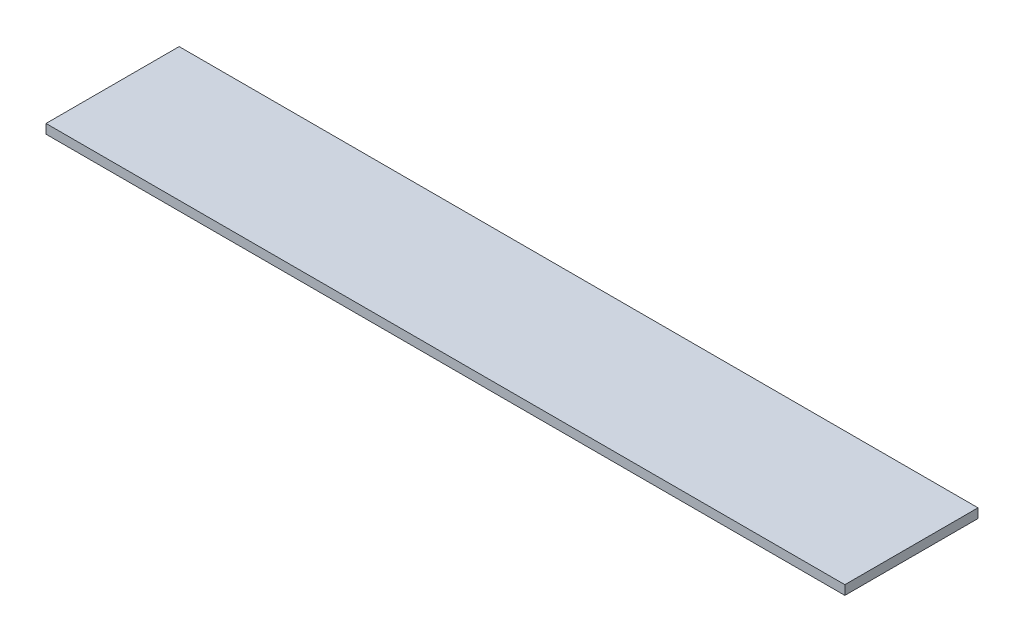
SolidWorks part; units mm, degrees
ref_plane "Front Plane" through (0, 0, 0) normal (0, 0, 1) x (1, 0, 0)
ref_plane "Top Plane" through (0, 0, 0) normal (0, 1, 0) x (1, 0, 0)
ref_plane "Right Plane" through (0, 0, 0) normal (1, 0, 0) x (0, 0, -1)
sketch "Sketch1" plane through (0, 0, 0) normal (0, 1, 0) x (1, 0, 0)
  line L1 (-30, -5) -> (30, -5)
  line L2 (-30, -5) -> (-30, 5)
  line L3 (-30, 5) -> (30, 5)
  line L4 (30, -5) -> (30, 5)
  line L5 (-30, -5) -> (30, 5) construction
  line L6 (-30, 5) -> (30, -5) construction
  point P0 (0, 0)
  dimension "D1" = 10
  dimension "D2" = 60
extrude "Boss-Extrude1" add sketch "Sketch1" along normal blind 0.7
